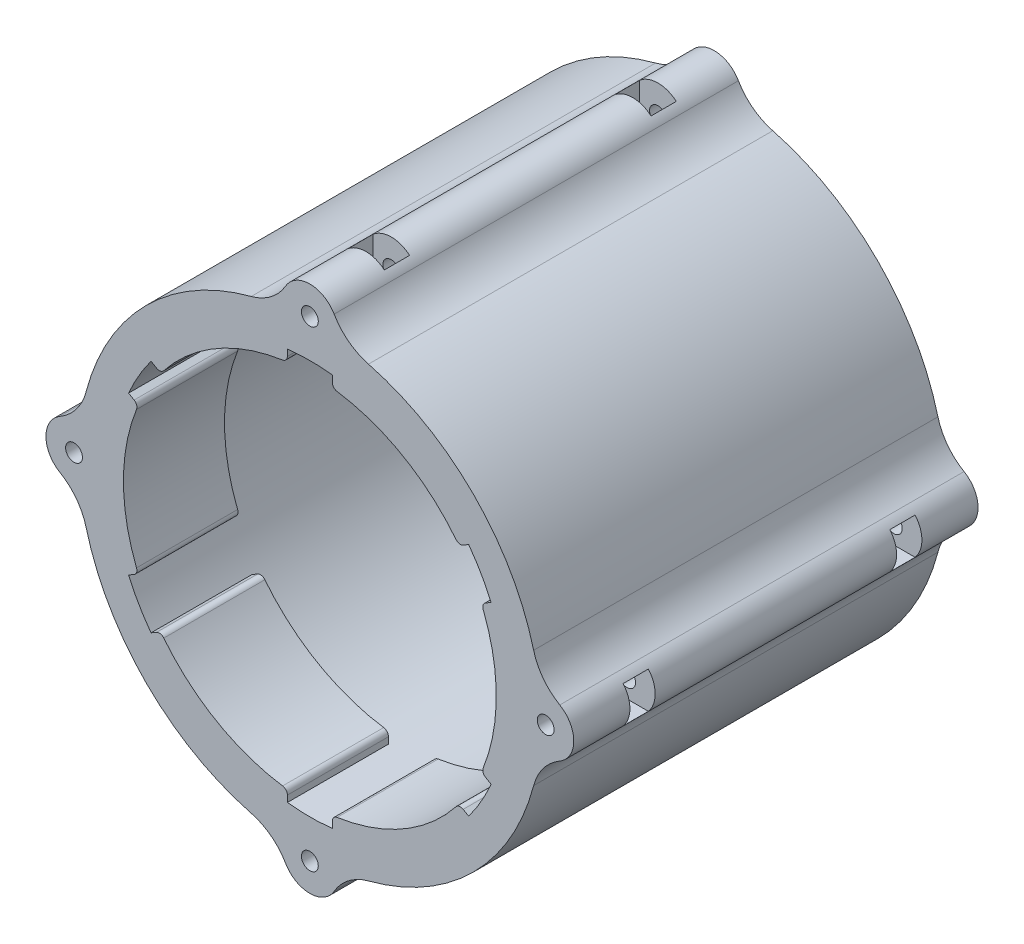
SolidWorks part; units mm, degrees
ref_plane "Ön Düzlem" through (0, 0, 0) normal (0, 0, 1) x (1, 0, 0)
ref_plane "Üst Düzlem" through (0, 0, 0) normal (0, 1, 0) x (1, 0, 0)
ref_plane "Sağ Düzlem" through (0, 0, 0) normal (1, 0, 0) x (0, 0, -1)
sketch "Çizim1" plane through (0, 0, 0) normal (0, 0, 1) x (1, 0, 0)
  circle A0 centre (0, 0) radius 35.2
  arc A1 (-39.8554, -10.4397) -> (-10.4397, -39.8554) centre (0, 0) ccw
  circle A6 centre (-42, 0) radius 1.5
  arc A7 (-44.5097, 4.3245) -> (-44.5097, -4.3245) centre (-42, 0) ccw
  circle A8 centre (0, 0) radius 41.2 construction
  arc A9 (-39.8554, -10.4397) -> (-44.5097, -4.3245) centre (-49.529, -12.9736) ccw
  arc A10 (-39.8554, 10.4397) -> (-44.5097, 4.3245) centre (-49.529, 12.9736) cw
  circle A11 centre (0, 42) radius 1.5
  arc A12 (4.3245, 44.5097) -> (-4.3245, 44.5097) centre (0, 42) ccw
  arc A13 (-10.4397, 39.8554) -> (-4.3245, 44.5097) centre (-12.9736, 49.529) ccw
  arc A14 (10.4397, 39.8554) -> (4.3245, 44.5097) centre (12.9736, 49.529) cw
  circle A15 centre (42, 0) radius 1.5
  arc A16 (44.5097, -4.3245) -> (44.5097, 4.3245) centre (42, 0) ccw
  arc A17 (39.8554, 10.4397) -> (44.5097, 4.3245) centre (49.529, 12.9736) ccw
  arc A18 (39.8554, -10.4397) -> (44.5097, -4.3245) centre (49.529, -12.9736) cw
  circle A19 centre (0, -42) radius 1.5
  arc A20 (-4.3245, -44.5097) -> (4.3245, -44.5097) centre (0, -42) ccw
  arc A21 (10.4397, -39.8554) -> (4.3245, -44.5097) centre (12.9736, -49.529) ccw
  arc A22 (-10.4397, -39.8554) -> (-4.3245, -44.5097) centre (-12.9736, -49.529) cw
  arc A23 (-10.4397, 39.8554) -> (-39.8554, 10.4397) centre (0, 0) ccw
  arc A24 (39.8554, 10.4397) -> (10.4397, 39.8554) centre (0, 0) ccw
  arc A25 (10.4397, -39.8554) -> (39.8554, -10.4397) centre (0, 0) ccw
  point P16 (0, 0)
  point P41 (0, 0)
  dimension "D1" = 70.4
  dimension "D3" = 5
  dimension "D4" = 3
  dimension "D5" = 42
  dimension "D6" = 10
  dimension "D2" = 6
  dimension "D7" = 4
extrude "Yükseklik-Ekstrüzyon1" add sketch "Çizim1" along normal blind 72
sketch "Çizim2" plane through (0, 0, 72) normal (0, 0, 1) x (1, 0, 0)
  line L0 (-4, 34.972) -> (-4, 32.9582)
  line L1 (4, 34.972) -> (4, 32.9582)
  line L2 (28.2866, 20.9501) -> (26.5426, 19.9432)
  line L3 (32.2866, 14.0219) -> (30.5426, 13.015)
  line L4 (32.2866, -14.0219) -> (30.5426, -13.015)
  line L5 (28.2866, -20.9501) -> (26.5426, -19.9432)
  line L6 (4, -34.972) -> (4, -32.9582)
  line L7 (-4, -34.972) -> (-4, -32.9582)
  line L8 (-28.2866, -20.9501) -> (-26.5426, -19.9432)
  line L9 (-32.2866, -14.0219) -> (-30.5426, -13.015)
  line L10 (-32.2866, 14.0219) -> (-30.5426, 13.015)
  line L11 (-28.2866, 20.9501) -> (-26.5426, 19.9432)
  arc A3 (-4, 34.972) -> (-28.2866, 20.9501) centre (0, 0) ccw
  arc A29 (-30.5426, 13.015) -> (-30.5426, -13.015) centre (0, 0) ccw
  arc A30 (-4, 32.9582) -> (-26.5426, 19.9432) centre (0, 0) ccw
  arc A31 (28.2866, 20.9501) -> (4, 34.972) centre (0, 0) ccw
  arc A34 (32.2866, -14.0219) -> (32.2866, 14.0219) centre (0, 0) ccw
  arc A36 (4, -34.972) -> (28.2866, -20.9501) centre (0, 0) ccw
  arc A38 (-28.2866, -20.9501) -> (-4, -34.972) centre (0, 0) ccw
  arc A40 (-32.2866, 14.0219) -> (-32.2866, -14.0219) centre (0, 0) ccw
  arc A41 (26.5426, 19.9432) -> (4, 32.9582) centre (0, 0) ccw
  arc A42 (30.5426, -13.015) -> (30.5426, 13.015) centre (0, 0) ccw
  arc A43 (4, -32.9582) -> (26.5426, -19.9432) centre (0, 0) ccw
  arc A44 (-26.5426, -19.9432) -> (-4, -32.9582) centre (0, 0) ccw
  point P55 (0, 0)
  dimension "D2" = 2
  dimension "D1" = 70.4
  dimension "D3" = 4
  dimension "D5" = 4
  dimension "D8" = 6
extrude "Yükseklik-Ekstrüzyon2" add sketch "Çizim2" against normal blind 18
ref_plane "Düzlem1" through (0, 0, 10) normal (0, 0, -1) x (-1, 0, 0)
sketch "Çizim3" plane through (0, 0, 10) normal (0, 0, -1) x (-1, 0, 0)
  line L0 (-3.262, -42) -> (-3.262, -48)
  line L1 (3.262, -42) -> (1.631, -39.175)
  line L2 (1.631, -39.175) -> (-1.631, -39.175)
  line L3 (-1.631, -39.175) -> (-3.262, -42)
  line L7 (3.262, -42) -> (3.262, -48)
  line L8 (3.262, -48) -> (-3.262, -48)
  line L9 (-2.4465, -43.4125) -> (-1.631, -44.825) [skipped]
  line L10 (0, -44.825) -> (1.631, -44.825) [skipped]
  line L11 (2.4465, -43.4125) -> (3.262, -42) [skipped]
  circle A0 centre (0, -42) radius 2.825 construction
  dimension "D1" = 3.262
  dimension "D2" = 6
  dimension "D3" = 6
  dimension "D4" = 3.262
  dimension "D5" = 3.262
extrude "Kes-Ekstrüzyon1" cut sketch "Çizim3" against normal blind 4.5
pattern_circular "Dairesel Kaplama1" count 4 every 90 about axis through (0, 0, 0) along (0, 0, 1) of "Kes-Ekstrüzyon1"
ref_plane "Düzlem2" through (0, 0, 36) normal (0, 0, -1) x (-1, 0, 0)
mirror "Aynalama1" about plane through (0, 0, 36) normal (0, 0, -1) of "Dairesel Kaplama1", "Kes-Ekstrüzyon1"
fillet "Radyus1" radius 1 12 edges at (4, 32.9582, 63) (-4, 32.9582, 63) (26.5426, -19.9432, 63) (30.5426, -13.015, 63) (-4, -32.9582, 63) (4, -32.9582, 63) (-26.5426, -19.9432, 63) (-30.5426, -13.015, 63) (-30.5426, 13.015, 63) (-26.5426, 19.9432, 63) (30.5426, 13.015, 63) (26.5426, 19.9432, 63)
